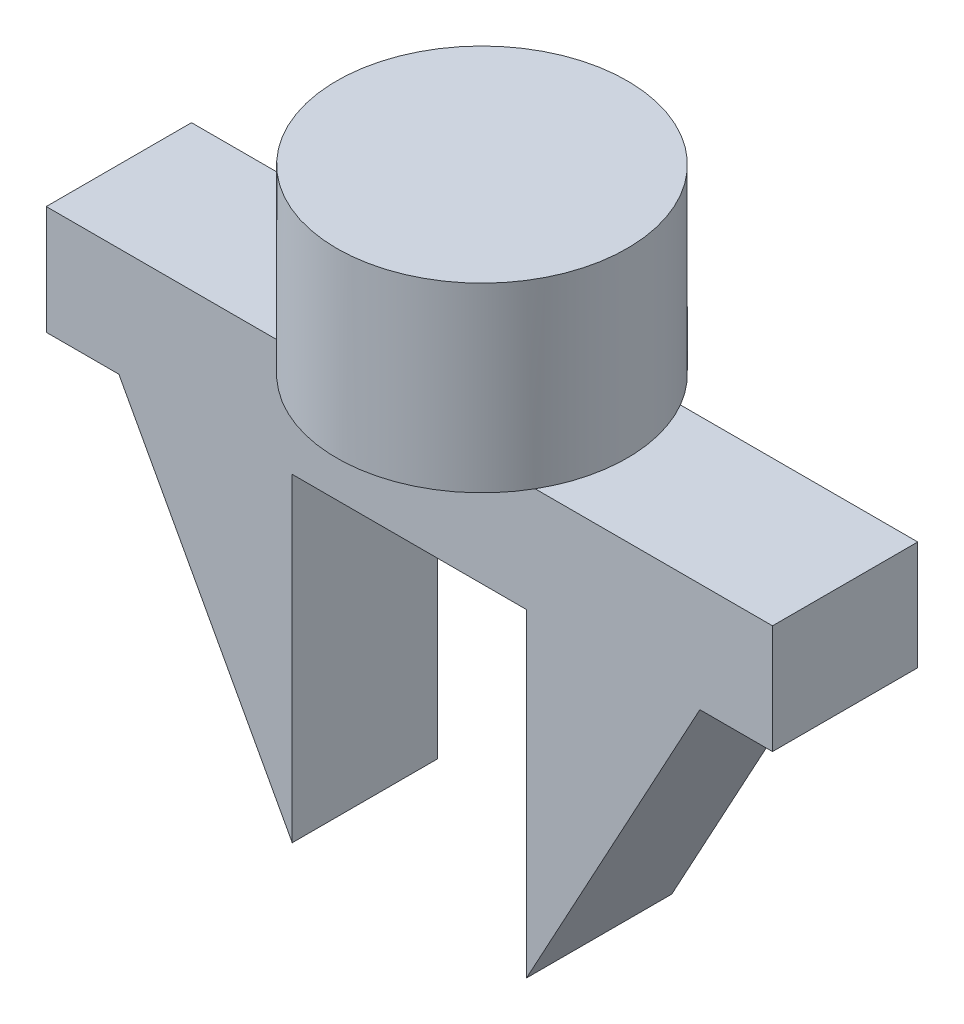
SolidWorks part; units mm, degrees
ref_plane "前视基准面" through (0, 0, 0) normal (0, 0, 1) x (1, 0, 0)
ref_plane "上视基准面" through (0, 0, 0) normal (0, 1, 0) x (1, 0, 0)
ref_plane "右视基准面" through (0, 0, 0) normal (1, 0, 0) x (0, 0, -1)
other "Configuration Table"
sketch "草图3" plane through (0, 0, 0) normal (0, 0, 1) x (1, 0, 0)
  line L0 (50, 0) -> (-50, 0)
  line L1 (-50, 0) -> (-50, -15)
  line L2 (-50, -15) -> (-40, -15)
  line L3 (-40, -15) -> (-16.1277, -58.9331)
  line L4 (-16.1277, -58.9331) -> (-16.1277, -15)
  line L5 (-16.1277, -15) -> (16.1277, -15)
  line L6 (0, -15) -> (0, 0)
  line L7 (16.1277, -58.9331) -> (16.1277, -15)
  line L8 (40, -15) -> (16.1277, -58.9331)
  line L9 (50, -15) -> (40, -15)
  line L10 (50, 0) -> (50, -15)
  dimension "D1" = 100
  dimension "D2" = 15
  dimension "D3" = 10
  dimension "D4" = 50
  dimension "D5" = 43.9331
  dimension "D6" = 32.2554
extrude "凸台-拉伸1" add sketch "草图3" along normal blind 20 contours L5 L6 L0 L1 L2 L3 L4 | L10 L0 L6 L5 L7 L8 L9
sketch "草图4" plane through (0, 0, 0) normal (0, 1, 0) x (1, 0, 0)
  line L0 (0, 0) -> (0, -20)
  line L1 (50, -20) -> (-50, -20) construction
  circle A0 centre (0, -10) radius 20
  line M3 (50, 0) -> (-50, 0)
  line M5 (-50, -20) -> (50, -20)
  dimension "D1" = 40
extrude "凸台-拉伸2" add sketch "草图4" along normal blind 25 contours A0 M5 | A0 L0 M3 M5 | A0 L0 M5 M3 | A0 M3
